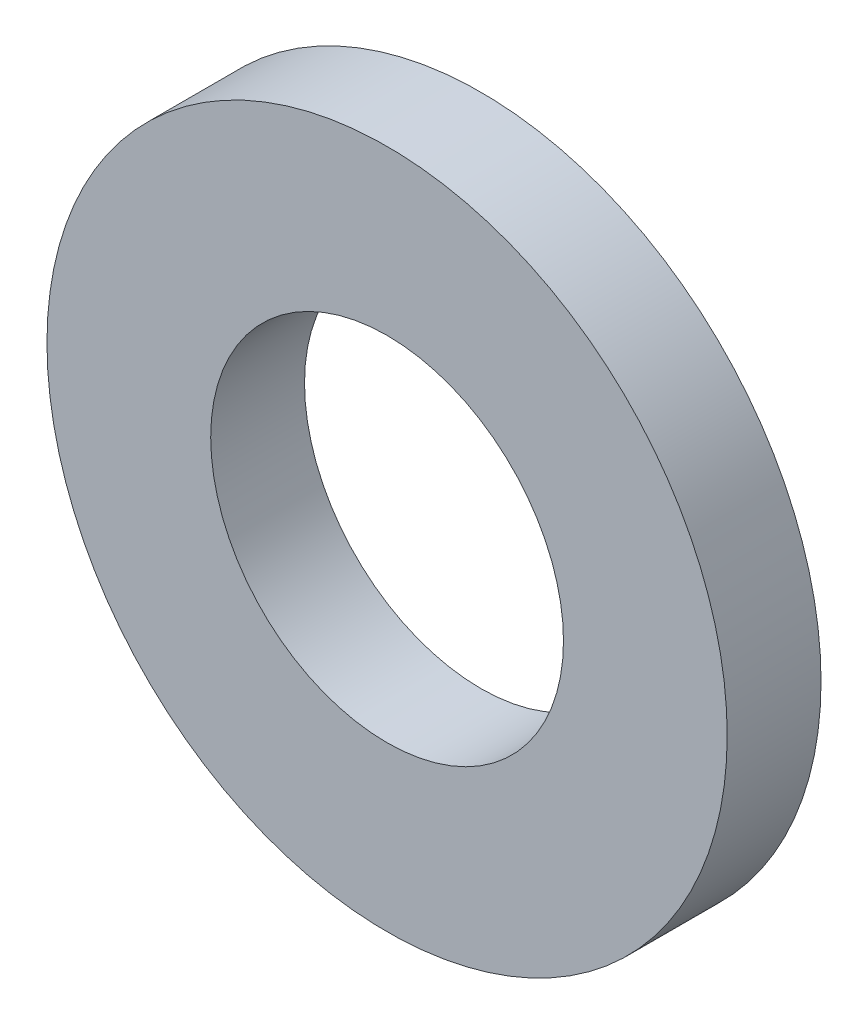
SolidWorks part; units mm, degrees
material "1060 Alloy"
ref_plane "Front Plane" through (0, 0, 0) normal (0, 0, 1) x (1, 0, 0)
ref_plane "Top Plane" through (0, 0, 0) normal (0, 1, 0) x (1, 0, 0)
ref_plane "Right Plane" through (0, 0, 0) normal (1, 0, 0) x (0, 0, -1)
sketch "Sketch1" plane through (0, 0, 0) normal (1, 0, 0) x (0, 0, -1)
  line L1 (0, 0) -> (12.7, 0) construction
  line L2 (0, 0) -> (0, 46.0375) construction
  line L3 (0, 46.0375) -> (12.7, 46.0375) construction
  line L4 (12.7, 0) -> (12.7, 46.0375) construction
  line L5 (0, 23.876) -> (12.7, 23.876)
  line L6 (0, 23.876) -> (0, 46.0375)
  line L7 (0, 46.0375) -> (12.7, 46.0375)
  line L8 (12.7, 23.876) -> (12.7, 46.0375)
  dimension "D1" = 46.0375
  dimension "D2" = 23.876
  dimension "D3" = 12.7
revolve "Revolve1" add sketch "Sketch1" angle 360 about L1
